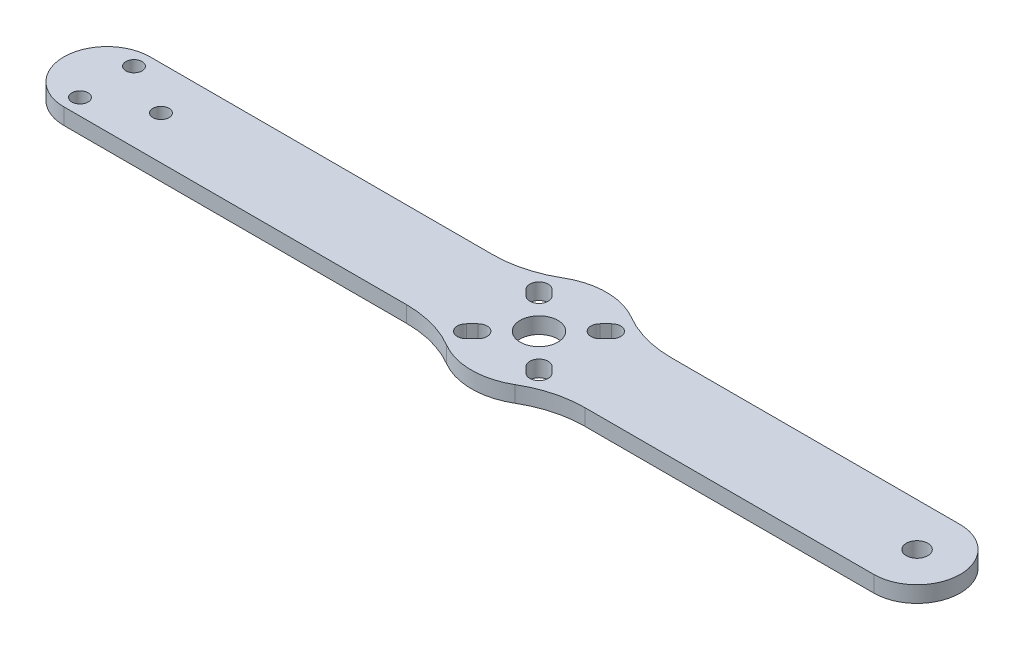
SolidWorks part; units mm, degrees
material "Thornel Mat VMA"
ref_plane "前视基准面" through (0, 0, 0) normal (0, 0, 1) x (1, 0, 0)
ref_plane "上视基准面" through (0, 0, 0) normal (0, 1, 0) x (1, 0, 0)
ref_plane "右视基准面" through (0, 0, 0) normal (1, 0, 0) x (0, 0, -1)
sketch "草图1" plane through (0, 0, 0) normal (0, 1, 0) x (1, 0, 0)
  line L0 (0, 0) -> (150, 0) construction
  line L1 (0, 8) -> (150, 8)
  line L2 (0, -8) -> (150, -8)
  arc A0 (0, 8) -> (0, -8) centre (0, 0) ccw
  arc A1 (150, -8) -> (150, 8) centre (150, 0) ccw
  point P3 (75, 0)
  dimension "D1" = 8
  dimension "D2" = 150
extrude "凸台-拉伸1" add sketch "草图1" along normal blind 3
sketch "草图8" plane through (0, 3, 0) normal (0, 1, 0) x (1, 0, 0)
  circle A0 centre (80, 0) radius 12.5
  dimension "D1" = 25
  dimension "D3" = 80
  dimension "D2" = 0
extrude "凸台-拉伸2" add sketch "草图8" against normal blind 3
sketch "草图2" plane through (0, 3, 0) normal (0, 1, 0) x (1, 0, 0)
  line L0 (80, 0) -> (85.6569, 5.6569) construction
  line L1 (150, 8) -> (89.6047, 8) construction
  line L2 (85.6569, 5.6569) -> (86.7175, 6.7175) construction
  line L5 (84.4562, 6.8575) -> (85.5169, 7.9181)
  line L6 (86.8575, 4.4562) -> (87.9181, 5.5169)
  line L7 (84.4562, -6.8575) -> (85.5169, -7.9181)
  line L8 (86.8575, -4.4562) -> (87.9181, -5.5169)
  line L9 (85.6569, -5.6569) -> (86.7175, -6.7175) construction
  line L10 (73.1425, -4.4562) -> (72.0819, -5.5169)
  line L11 (75.5438, -6.8575) -> (74.4831, -7.9181)
  line L12 (74.3431, -5.6569) -> (73.2825, -6.7175) construction
  line L13 (75.5438, 6.8575) -> (74.4831, 7.9181)
  line L14 (73.1425, 4.4562) -> (72.0819, 5.5169)
  line L15 (74.3431, 5.6569) -> (73.2825, 6.7175) construction
  circle A0 centre (80, 0) radius 3.5
  arc A7 (84.4562, 6.8575) -> (86.8575, 4.4562) centre (85.6569, 5.6569) ccw
  arc A8 (87.9181, 5.5169) -> (85.5169, 7.9181) centre (86.7175, 6.7175) ccw
  arc A9 (86.8575, -4.4562) -> (84.4562, -6.8575) centre (85.6569, -5.6569) ccw
  arc A10 (85.5169, -7.9181) -> (87.9181, -5.5169) centre (86.7175, -6.7175) ccw
  arc A11 (75.5438, -6.8575) -> (73.1425, -4.4562) centre (74.3431, -5.6569) ccw
  arc A12 (72.0819, -5.5169) -> (74.4831, -7.9181) centre (73.2825, -6.7175) ccw
  arc A13 (73.1425, 4.4562) -> (75.5438, 6.8575) centre (74.3431, 5.6569) ccw
  arc A14 (74.4831, 7.9181) -> (72.0819, 5.5169) centre (73.2825, 6.7175) ccw
  point P3 (86.1872, 6.1872)
  point P12 (0, 0)
  point P16 (80, 0)
  point P17 (86.1872, -6.1872)
  point P24 (73.8128, -6.1872)
  point P31 (73.8128, 6.1872)
  point P37 (80, 0)
  dimension "D2" = 8
  dimension "D3" = 45
  dimension "D4" = 9.5
  dimension "D6" = 7
  dimension "D1" = 80
  dimension "D7" = 0
  dimension "D8" = 0
  dimension "D5" = 4
extrude "切除-拉伸1" cut sketch "草图2" against normal through all
sketch "草图5" plane through (0, 3, 0) normal (0, 1, 0) x (1, 0, 0)
  circle A0 centre (10, 0) radius 1.5
  circle A1 centre (0, 5) radius 1.5
  circle A2 centre (0, -5) radius 1.5
  point P6 (0, 0)
  dimension "D1" = 3
  dimension "D2" = 3
  dimension "D3" = 3
  dimension "D4" = 5
  dimension "D5" = 5
  dimension "D6" = 10
extrude "切除-拉伸2" cut sketch "草图5" against normal through all
fillet "圆角3" radius 20 4 edges at (70.3953, 1.5, 8) (89.6047, 1.5, 8) (89.6047, 1.5, -8) (70.3953, 1.5, -8)
sketch "草图9" plane through (0, 3, 0) normal (0, 1, 0) x (1, 0, 0)
  circle A0 centre (150, 0) radius 2
  dimension "D1" = 4
extrude "切除-拉伸3" cut sketch "草图9" against normal through all
